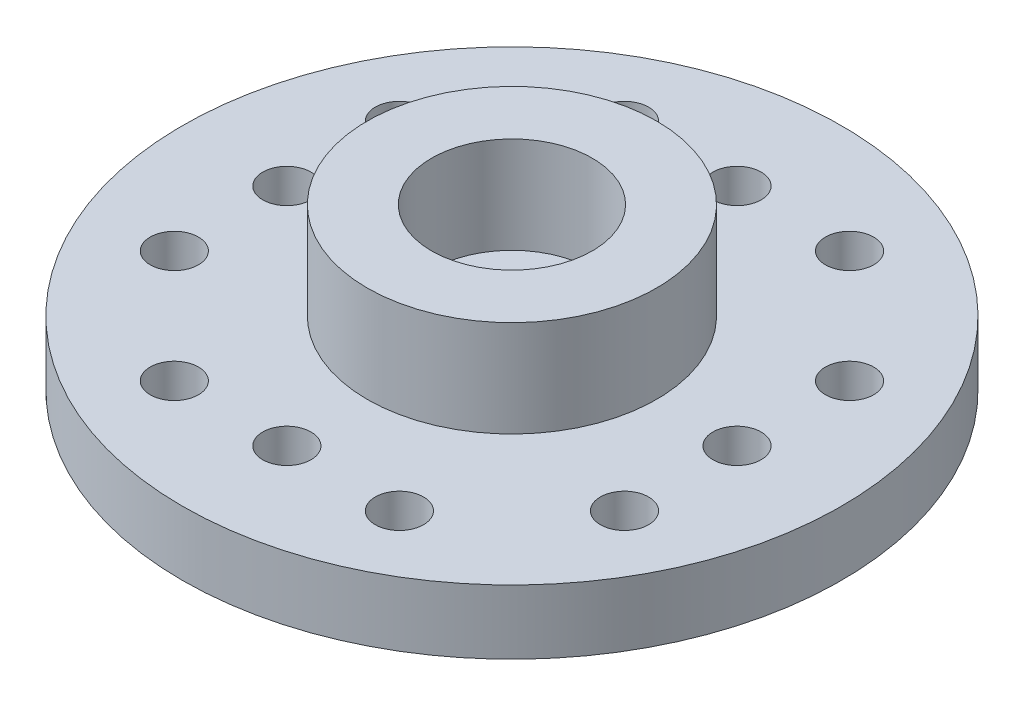
SolidWorks part; units mm, degrees
ref_plane "Front Plane" through (0, 0, 0) normal (0, 0, 1) x (1, 0, 0)
ref_plane "Top Plane" through (0, 0, 0) normal (0, 1, 0) x (1, 0, 0)
ref_plane "Right Plane" through (0, 0, 0) normal (1, 0, 0) x (0, 0, -1)
sketch "Sketch1" plane through (0, 0, 0) normal (0, 1, 0) x (1, 0, 0)
  circle A0 centre (0, 0) radius 10.25
  dimension "D1" = 20.5
extrude "Boss-Extrude1" add sketch "Sketch1" along normal blind 2
sketch "Sketch2" plane through (0, 2, 0) normal (0, 1, 0) x (1, 0, 0)
  circle A0 centre (0, 0) radius 4.5
  circle A1 centre (0, 0) radius 2.5
  dimension "D1" = 9
  dimension "D2" = 5
extrude "Boss-Extrude2" add sketch "Sketch2" along normal blind 3
sketch "Sketch3" plane through (0, 0, 0) normal (0, -1, 0) x (1, 0, 0)
  circle A0 centre (0, 0) radius 1.5
  dimension "D1" = 3
extrude "Cut-Extrude1" cut sketch "Sketch3" against normal through all
sketch "Sketch4" plane through (0, 0, 0) normal (0, -1, 0) x (1, 0, 0)
  line L0 (15.6291, 0) -> (-14.3499, 0) construction
  line L1 (-7, -7) -> (7, -7) construction
  line L2 (-7, -7) -> (-7, 7) construction
  line L3 (-7, 7) -> (7, 7) construction
  line L4 (7, -7) -> (7, 7) construction
  line L5 (-7, -7) -> (7, 7) construction
  line L6 (-7, 7) -> (7, -7) construction
  line L7 (0, -11.7775) -> (0, 10.8597) construction
  circle A0 centre (0, 7) radius 0.75
  circle A1 centre (-3.5, 7) radius 0.75
  circle A2 centre (3.5, 7) radius 0.75
  point P0 (0, 0)
  point P17 (0, 0)
  dimension "D2" = 1.5
  dimension "D3" = 3.5
  dimension "D1" = 14
extrude "Cut-Extrude2" cut sketch "Sketch4" against normal through all
pattern_circular "CirPattern1" count 4 over 360 about axis through (0, 0, 0) along (0, 1, 0) of "Cut-Extrude2"
equation "\"20.5.00mm\"=20"
